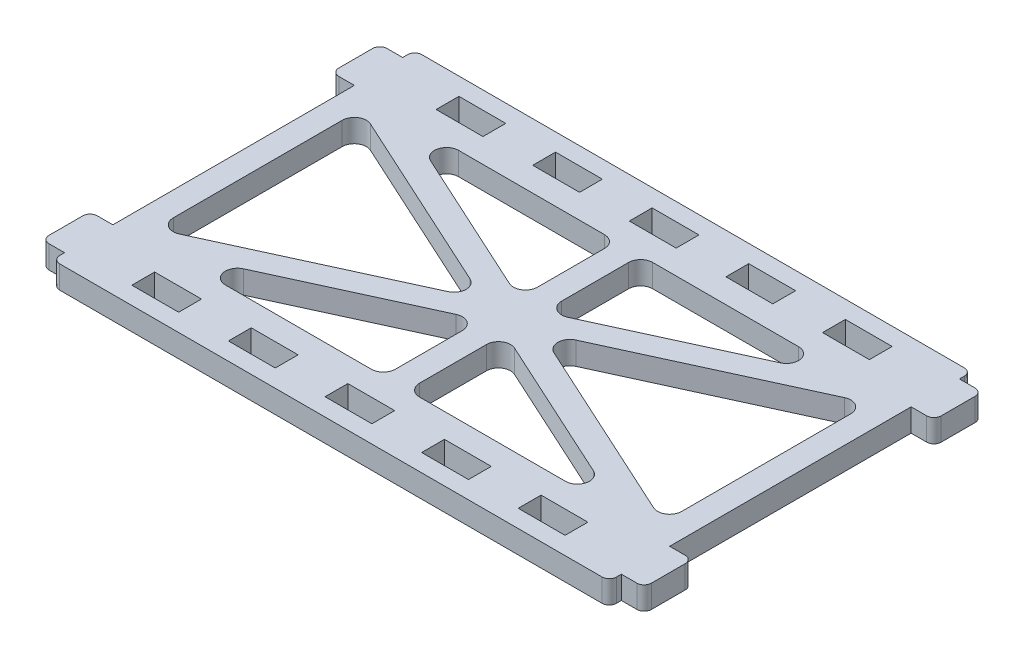
SolidWorks part; units mm, degrees
ref_plane "Front Plane" through (0, 0, 0) normal (0, 0, 1) x (1, 0, 0)
ref_plane "Top Plane" through (0, 0, 0) normal (0, 1, 0) x (1, 0, 0)
ref_plane "Right Plane" through (0, 0, 0) normal (1, 0, 0) x (0, 0, -1)
sketch "Sketch1" plane through (0, 0, 0) normal (0, 1, 0) x (1, 0, 0)
  line L1 (76.2, -50.8) -> (-76.2, -50.8) construction
  line L2 (76.2, -50.8) -> (76.2, 50.8) construction
  line L3 (76.2, 50.8) -> (-76.2, 50.8) construction
  line L4 (-76.2, -50.8) -> (-76.2, 50.8) construction
  line L5 (76.2, -50.8) -> (-76.2, 50.8) construction
  line L6 (76.2, 50.8) -> (-76.2, -50.8) construction
  line L7 (73.2, -47.625) -> (-73.2, -47.625)
  line L8 (73.2, -47.625) -> (73.2, 47.625)
  line L9 (73.2, 47.625) -> (-73.2, 47.625)
  line L10 (-73.2, -47.625) -> (-73.2, 47.625)
  line L11 (73.2, -47.625) -> (-73.2, 47.625) construction
  line L12 (73.2, 47.625) -> (-73.2, -47.625) construction
  line L13 (-73.2, -50.8) -> (-79.2, -50.8) construction
  line L14 (-73.2, -50.8) -> (-73.2, 50.8) construction
  line L15 (-73.2, 50.8) -> (-79.2, 50.8) construction
  line L16 (-79.2, -50.8) -> (-79.2, 50.8) construction
  line L17 (-73.2, -50.8) -> (-79.2, 50.8) construction
  line L18 (-73.2, 50.8) -> (-79.2, -50.8) construction
  line L19 (73.2, -50.8) -> (79.2, -50.8) construction
  line L20 (73.2, -50.8) -> (73.2, 50.8) construction
  line L21 (73.2, 50.8) -> (79.2, 50.8) construction
  line L22 (79.2, -50.8) -> (79.2, 50.8) construction
  line L23 (73.2, -50.8) -> (79.2, 50.8) construction
  line L24 (73.2, 50.8) -> (79.2, -50.8) construction
  point P0 (0, 0)
  point P6 (0, 0)
  point P11 (-76.2, 0)
  point P16 (76.2, 0)
  dimension "D1" = 152.4
  dimension "D2" = 101.6
  dimension "D4" = 6
  dimension "D5" = 95.25
extrude "Boss-Extrude1" add sketch "Sketch1" along normal mid plane 6
sketch "Sketch2" plane through (0, 3, 0) normal (0, 1, 0) x (1, 0, 0)
  line L0 (-73.2, 47.625) -> (-73.2, -47.625) construction
  line L1 (-79.2, 44.45) -> (-73.2, 44.45)
  line L2 (-79.2, 44.45) -> (-79.2, 31.75)
  line L3 (-79.2, 31.75) -> (-73.2, 31.75)
  line L4 (-73.2, 44.45) -> (-73.2, 31.75)
  line L5 (-79.2, 44.45) -> (-73.2, 31.75) construction
  line L6 (-79.2, 31.75) -> (-73.2, 44.45) construction
  line L7 (-79.2, -31.75) -> (-73.2, -31.75)
  line L8 (-79.2, -31.75) -> (-79.2, -44.45)
  line L9 (-79.2, -44.45) -> (-73.2, -44.45)
  line L10 (-73.2, -31.75) -> (-73.2, -44.45)
  line L11 (-79.2, -31.75) -> (-73.2, -44.45) construction
  line L12 (-79.2, -44.45) -> (-73.2, -31.75) construction
  line L13 (-76.2, 38.1) -> (-76.2, -38.1) construction
  line L14 (-76.2, 0) -> (0, 0) construction
  point P0 (-76.2, 38.1)
  point P5 (-76.2, -38.1)
  dimension "D1" = 12.7
  dimension "D2" = 6
  dimension "D3" = 76.2
extrude "Boss-Extrude2" add sketch "Sketch2" against normal up to surface (6 mm away) up to face at (0, -3, 0)
mirror "Mirror1" about plane through (0, 0, 0) normal (1, 0, 0) of "Boss-Extrude2"
sketch "Sketch3" plane through (0, 3, 0) normal (0, 1, 0) x (1, 0, 0)
  line L0 (0, 0) -> (0, 22.4302) construction
  line L5 (0, 0) -> (32.0176, 0) construction
  line L7 (73.2, 47.625) -> (-73.2, 47.625) construction
  line L8 (-6.1595, 43.005) -> (6.1595, 43.005)
  line L9 (-6.1595, 43.005) -> (-6.1595, 37.005)
  line L10 (-6.1595, 37.005) -> (6.1595, 37.005)
  line L11 (6.1595, 43.005) -> (6.1595, 37.005)
  line L12 (-6.1595, -37.005) -> (6.1595, -37.005)
  line L13 (6.1595, -43.005) -> (6.1595, -37.005)
  line L14 (-6.1595, -43.005) -> (6.1595, -43.005)
  line L15 (-6.1595, -43.005) -> (-6.1595, -37.005)
  point P8 (0, 37.005)
  point P9 (-6.1595, 40.005)
  dimension "D1" = 6
  dimension "D2" = 12.319
  dimension "D3" = 7.62
extrude "Cut-Extrude1" cut sketch "Sketch3" against normal through all both and the other way through all
pattern_linear "LPattern3" count 3 spacing 25.4 along (1, 0, 0) count 3 spacing 25.4 along (-1, 0, 0) of "Cut-Extrude1"
sketch "Sketch4" plane through (0, 3, 0) normal (0, 1, 0) x (1, 0, 0)
  line L1 (-73.2, 37.005) -> (73.2, 37.005) construction
  line L2 (-73.2, 37.005) -> (-73.2, -37.005) construction
  line L3 (-73.2, -37.005) -> (73.2, -37.005) construction
  line L4 (73.2, 37.005) -> (73.2, -37.005) construction
  line L5 (73.2, -31.75) -> (73.2, 31.75) construction
  line L6 (56.9595, -37.005) -> (44.6405, -37.005) construction
  line L7 (-73.2, 31.75) -> (-73.2, -31.75) construction
  line L14 (-66.85, 30.655) -> (66.85, 30.655)
  line L17 (66.85, 30.655) -> (66.85, -30.655)
  line L18 (-66.85, -30.655) -> (66.85, -30.655)
  line L19 (-66.85, 30.655) -> (-66.85, -30.655)
  line L20 (-66.85, 30.655) -> (66.85, -30.655) construction
  line L21 (66.85, 30.655) -> (-66.85, -30.655) construction
  line L22 (0, 30.655) -> (0, -30.655) construction
  line L23 (-68.1734, 27.769) -> (65.5266, -33.541)
  line L24 (-3.175, 30.655) -> (-3.175, -30.655)
  line L25 (65.5266, 33.541) -> (-68.1734, -27.769)
  line L26 (-65.5266, 33.541) -> (68.1734, -27.769)
  line L28 (-56.9595, 37.005) -> (-44.6405, 37.005) construction
  line L30 (3.175, 30.655) -> (3.175, -30.655)
  line L32 (68.1734, 27.769) -> (-65.5266, -33.541)
  dimension "D1" = 6.35
  dimension "D2" = 3.175
  dimension "D3" = 3.175
extrude "Cut-Extrude2" cut sketch "Sketch4" against normal through all contours L25 L23 L19 | L14 L26 L24 | L14 L30 L25 | L17 L32 L26 | L23 L30 L18 | L24 L32 L18
fillet "Fillet1" radius 3.175 18 edges at (-3.175, 0, 30.655) (-59.2329, 0, 30.655) (-3.175, 0, 4.9488) (-66.85, 0, 27.1621) (-66.85, 0, -27.1621) (-7.6171, 0, 0) (-3.175, 0, -30.655) (-59.2329, 0, -30.655) (-3.175, 0, -4.9488) (59.2329, 0, -30.655) (3.175, 0, -30.655) (3.175, 0, -4.9488) (66.85, 0, 27.1621) (66.85, 0, -27.1621) (7.6171, 0, 0) (59.2329, 0, 30.655) (3.175, 0, 30.655) (3.175, 0, 4.9488)
fillet "Fillet2" radius 1.905 12 edges at (-73.2, 0, 47.625) (-79.2, 0, 44.45) (-79.2, 0, 31.75) (-79.2, 0, -31.75) (-79.2, 0, -44.45) (-73.2, 0, -47.625) (79.2, 0, -44.45) (73.2, 0, -47.625) (79.2, 0, -31.75) (79.2, 0, 31.75) (79.2, 0, 44.45) (73.2, 0, 47.625)
